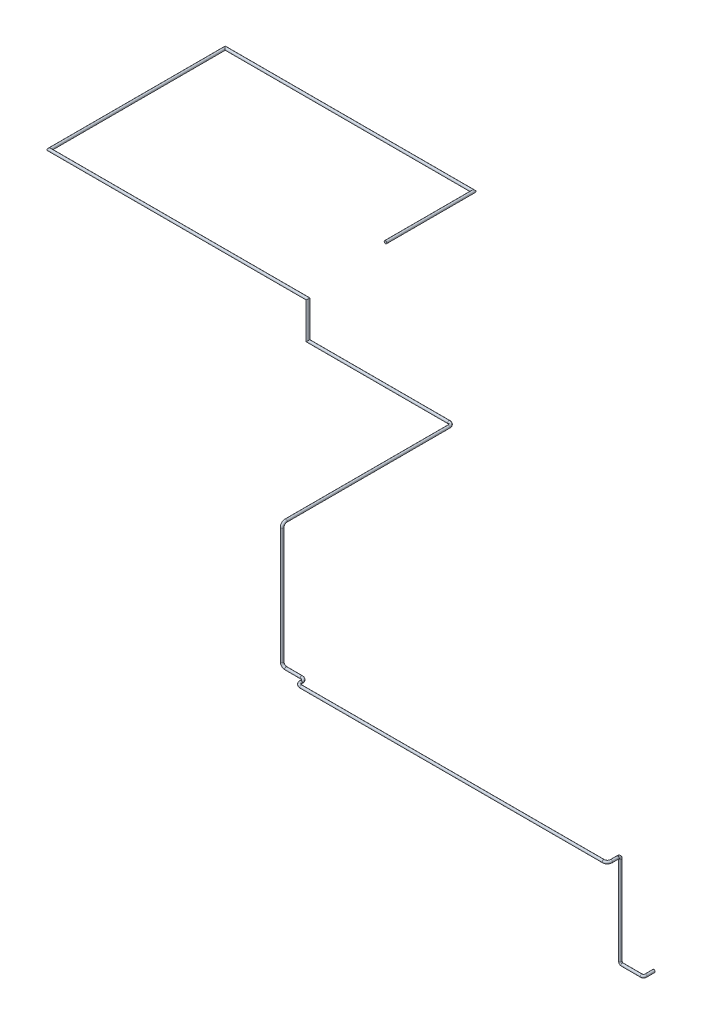
SolidWorks part; units mm, degrees
ref_plane "Alzado" through (0, 0, 0) normal (0, 0, 1) x (1, 0, 0)
ref_plane "Planta" through (0, 0, 0) normal (0, 1, 0) x (1, 0, 0)
ref_plane "Vista lateral" through (0, 0, 0) normal (1, 0, 0) x (0, 0, -1)
sketch "Croquis1" plane through (0, 0, 0) normal (0, 0, 1) x (1, 0, 0)
  circle A0 centre (0, 0) radius 25.4
  dimension "D1" = 50.8
extrude "Saliente-Extruir1" add sketch "Croquis1" along normal blind 100
sketch3d "Croquis3D2"
  line L0 (0, 0, 100) -> (0, 0, 125)
  line L1 (0, 0, 100) -> (0, 0, 0) construction
  line L2 (-75, 0, 200) -> (-5925, 0, 200)
  line L3 (-6000, 0, 125) -> (-6000, 0, 115)
  line L4 (-6075, 0, 40) -> (-6375, 0, 40)
  line L5 (-6450, 75, 40) -> (-6450, 2325, 40)
  line L6 (-6450, 2400, -35) -> (-6450, 2400, -3185)
  line L7 (-6525, 2400, -3260) -> (-9250, 2400, -3260)
  line L8 (-9250, 2400, -3260) -> (-9250, 3100, -3260)
  line L9 (-9250, 3100, -3260) -> (-14250, 3100, -3260)
  line L10 (-14250, 3100, -3260) -> (-14250, 3100, -6660)
  line L11 (-14250, 3100, -6660) -> (-9450, 3100, -6660)
  line L12 (-9450, 3100, -6660) -> (-9450, 3100, -4960)
  arc A0 (-6450, 2400, -3185) -> (-6525, 2400, -3260) centre (-6525, 2400, -3185) ccw
  arc A1 (-6450, 2325, 40) -> (-6450, 2400, -35) centre (-6450, 2325, -35) ccw
  arc A2 (-6375, 0, 40) -> (-6450, 75, 40) centre (-6375, 75, 40) ccw
  arc A3 (-6000, 0, 115) -> (-6075, 0, 40) centre (-6075, 0, 115) ccw
  arc A4 (-5925, 0, 200) -> (-6000, 0, 125) centre (-5925, 0, 125) ccw
  arc A5 (0, 0, 125) -> (-75, 0, 200) centre (-75, 0, 125) ccw
  point P12 (-6450, 2400, -3260)
  point P13 (-6525, 2475, -3185)
  point P16 (-6450, 2400, 40)
  point P17 (-6525, 2325, -35)
  point P20 (-6450, 0, 40)
  point P21 (-6375, 75, -35)
  point P24 (-6000, 0, 40)
  point P25 (-6075, 75, 115)
  point P28 (-6000, 0, 200)
  point P29 (-5925, -75, 125)
  point P32 (0, 0, 200)
  point P33 (-75, -75, 125)
  dimension "D8" = 75
  dimension "D1" = 100
  dimension "D2" = 6000
  dimension "D3" = 160
  dimension "D4" = 450
  dimension "D5" = 2400
  dimension "D6" = 3300
  dimension "D7" = 2800
  dimension "D9" = 700
  dimension "D10" = 5000
  dimension "D11" = 3400
  dimension "D12" = 4800
  dimension "D13" = 1700
sketch "Croquis6" plane through (0, 0, 100) normal (0, 0, 1) x (1, 0, 0)
  circle A0 centre (0, 0) radius 25.4
  dimension "D1" = 50.8
sweep "Barrer2" add profiles "Croquis6" path "Croquis3D2"
sketch3d "Croquis3D3"
  line L0 (0, 0, 0) -> (0, 0, -10)
  line L1 (0, -40, -50) -> (0, -1760, -50)
  line L2 (40, -1800, -50) -> (410, -1800, -50)
  line L3 (450, -1800, -90) -> (450, -1800, -250)
  arc A0 (410, -1800, -50) -> (450, -1800, -90) centre (410, -1800, -90) ccw
  arc A1 (0, -1760, -50) -> (40, -1800, -50) centre (40, -1760, -50) ccw
  arc A2 (0, 0, -10) -> (0, -40, -50) centre (0, -40, -10) ccw
  point P8 (450, -1800, -50)
  point P9 (410, -1760, -90)
  point P12 (0, -1800, -50)
  point P13 (40, -1760, -10)
  point P16 (0, 0, -50)
  point P17 (-40, -40, -10)
  dimension "D5" = 40
  dimension "D1" = 50
  dimension "D2" = 1800
  dimension "D3" = 450
  dimension "D4" = 200
sketch "Croquis7" plane through (0, 0, 0) normal (0, 0, -1) x (-1, 0, 0)
  circle A0 centre (0, 0) radius 25
  dimension "D1" = 50
sweep "Barrer3" add profiles "Croquis7" path "Croquis3D3"
